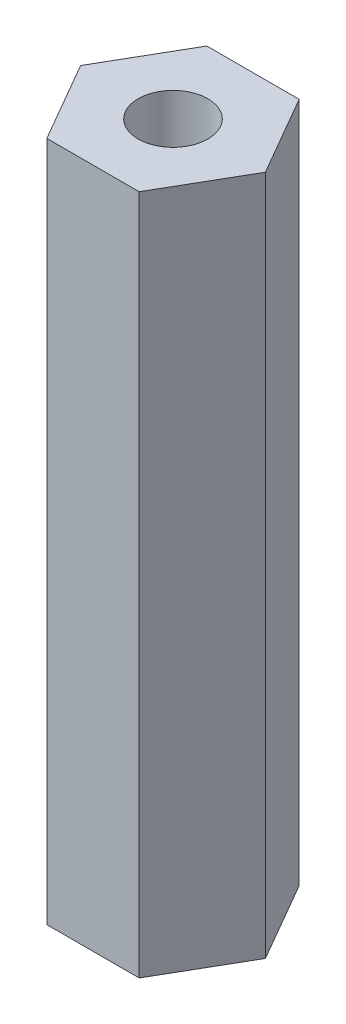
SolidWorks part; units mm, degrees
ref_plane "Front Plane" through (0, 0, 0) normal (0, 0, 1) x (1, 0, 0)
ref_plane "Top Plane" through (0, 0, 0) normal (0, 1, 0) x (1, 0, 0)
ref_plane "Right Plane" through (0, 0, 0) normal (1, 0, 0) x (0, 0, -1)
ref_plane "Plane1" through (0, 20, 0) normal (0, 1, 0) x (1, 0, 0)
sketch "Sketch1" plane through (0, 20, 0) normal (0, 1, 0) x (1, 0, 0)
  line L0 (1.3568, -2.35) -> (2.7135, 0)
  line L1 (2.7135, 0) -> (1.3568, 2.35)
  line L2 (1.3568, 2.35) -> (-1.3568, 2.35)
  line L3 (-1.3568, 2.35) -> (-2.7135, 0)
  line L4 (-2.7135, 0) -> (-1.3568, -2.35)
  line L5 (-1.3568, -2.35) -> (1.3568, -2.35)
  circle A0 centre (0, 0) radius 2.7135 construction
  dimension "D1" = 4.7
extrude "Boss-Extrude1" add sketch "Sketch1" against normal blind 20
ref_plane "Plane2" through (0, 0, 0) normal (0, 0, -1) x (-1, 0, 0)
hole_wizard "Tap Drill for M2.5x0.45 Tap1" positions "Sketch4" profile "Sketch3" hole size "M2.5x0.45" standard "ANSI Metric"
sketch "Sketch4" plane through (0, 20, 0) normal (0, 1, 0) x (1, 0, 0)
  point P0 (0, 0)
sketch "Sketch3" plane through (0, 20, 0) normal (1, 0, 0) x (0, 0, 1)
  line L0 (0, 0) -> (0, 21)
  line L1 (0, 21) -> (1.025, 21)
  line L2 (1.025, 21) -> (1.025, 0)
  line L5 (1.025, 0) -> (0, 0)
  line L10 (0, 21) -> (-1.025, 21) construction
  line L11 (0, -6.35) -> (0, 107.95) construction
  dimension "Hole Dia." = 2.05
  dimension "Hole Depth" = 21
  dimension "Drill Angle" = 180
